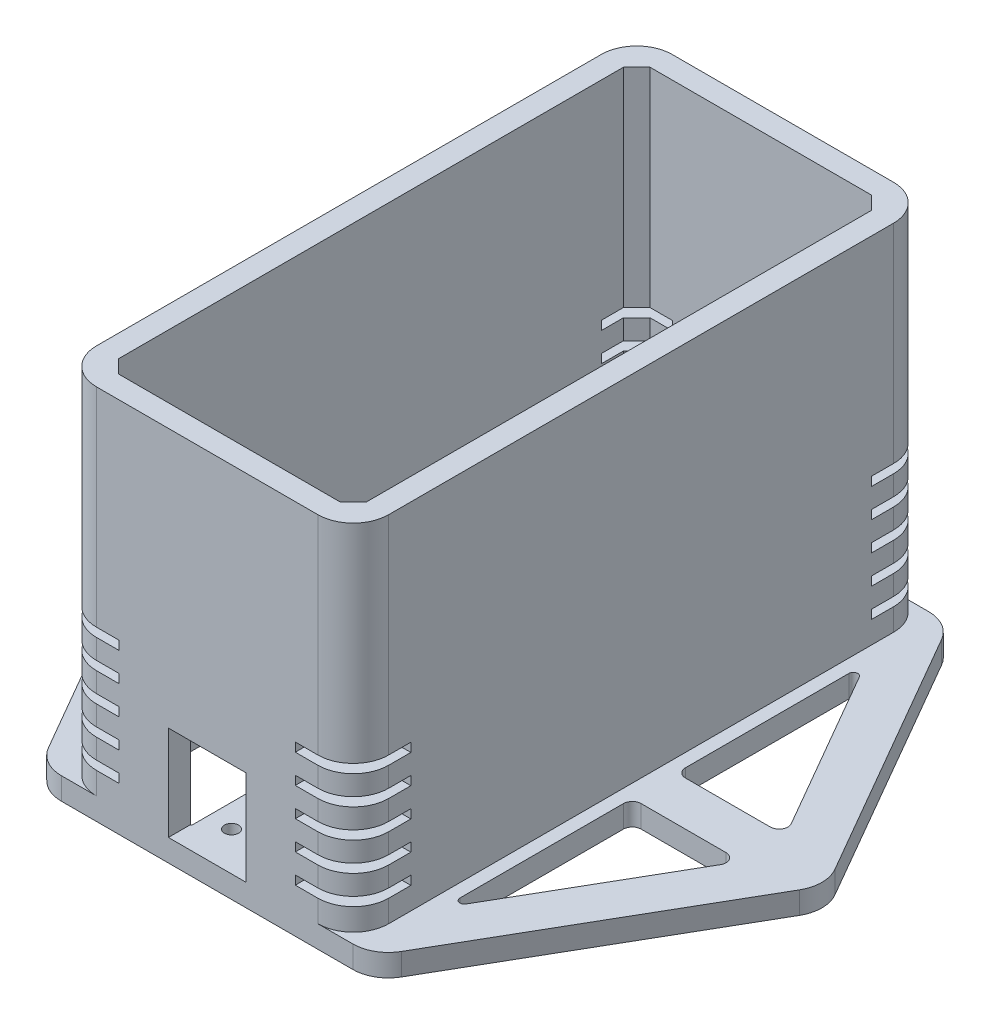
SolidWorks part; units mm, degrees
ref_plane "Front Plane" through (0, 0, 0) normal (0, 0, 1) x (1, 0, 0)
ref_plane "Top Plane" through (0, 0, 0) normal (0, 1, 0) x (1, 0, 0)
ref_plane "Right Plane" through (0, 0, 0) normal (1, 0, 0) x (0, 0, -1)
sketch "Sketch1" plane through (0, 0, 0) normal (0, 1, 0) x (1, 0, 0)
  line L1 (-75.0555, 0) -> (-37.5278, -65)
  line L2 (-37.5278, -65) -> (37.5278, -65)
  line L3 (37.5278, -65) -> (75.0555, 0)
  line L4 (75.0555, 0) -> (37.5278, 65)
  line L5 (37.5278, 65) -> (-37.5278, 65)
  line L6 (-37.5278, 65) -> (-75.0555, 0)
  circle A0 centre (0, 0) radius 65 construction
  circle A1 centre (0, 0) radius 50 construction
  dimension "D2" = 100
  dimension "D1" = 130
extrude "Boss-Extrude1" add sketch "Sketch1" along normal blind 5
fillet "Fillet1" radius 8 6 edges at (37.5278, 2.5, -65) (75.0555, 2.5, 0) (37.5278, 2.5, 65) (-37.5278, 2.5, 65) (-75.0555, 2.5, 0) (-37.5278, 2.5, -65)
sketch "Sketch3" plane through (0, 5, 0) normal (0, 1, 0) x (1, 0, 0)
  line L0 (-32.909, -65) -> (32.909, -65) construction
  line L1 (-25, 65) -> (25, 65)
  line L2 (-33, 57) -> (-33, -57)
  line L3 (-25, -65) -> (25, -65)
  line L4 (33, 57) -> (33, -57)
  line L5 (-33, 65) -> (33, -65) construction
  line L6 (-33, -65) -> (33, 65) construction
  arc A0 (33, 57) -> (25, 65) centre (25, 57) ccw
  arc A1 (33, -57) -> (25, -65) centre (25, -57) cw
  arc A2 (-25, -65) -> (-33, -57) centre (-25, -57) cw
  arc A3 (-25, 65) -> (-33, 57) centre (-25, 57) ccw
  point P0 (0, 0)
  dimension "D1" = 8
  dimension "D2" = 50
extrude "Boss-Extrude2" add sketch "Sketch3" along normal blind 80
sketch "Sketch4" plane through (0, 85, 0) normal (0, 1, 0) x (1, 0, 0)
  line L0 (-28, 57) -> (-25, 60)
  line L1 (25, 60) -> (28, 57)
  line L2 (28, -57) -> (25, -60)
  line L3 (-28, -57) -> (-25, -60)
  line L9 (-25, -60) -> (25, -60)
  line L10 (28, -57) -> (28, 57)
  line L11 (25, 60) -> (-25, 60)
  line L12 (-28, 57) -> (-28, -57)
  line L13 (-25, -60) -> (25, -60)
  line L14 (28, -57) -> (28, 57)
  line L15 (25, 60) -> (-25, 60)
  line L16 (-28, 57) -> (-28, -57)
  arc A9 (-28, -57) -> (-25, -60) centre (-25, -57) ccw
  arc A10 (25, -60) -> (28, -57) centre (25, -57) ccw
  arc A11 (28, 57) -> (25, 60) centre (25, 57) ccw
  arc A12 (-25, 60) -> (-28, 57) centre (-25, 57) ccw
  dimension "D1" = 5
extrude "Cut-Extrude1" cut sketch "Sketch4" against normal up to surface (85 mm away) up to face at (0, 0, 0)
sketch "Sketch8" plane through (0, 0, 0) normal (0, 1, 0) x (1, 0, 0)
  line L0 (0, 40) -> (0, 25) construction
  line L1 (0, 55) -> (0, 65) construction
  line L2 (9.5263, 26.5) -> (24.2487, 52) construction
  line L3 (22.5167, 55) -> (-22.5167, 55) construction
  line L4 (-24.2487, 52) -> (-9.5263, 26.5) construction
  line L5 (-12.5, 0) -> (-62.3346, 0) construction
  line L36 (6.9282, 25) -> (-6.9282, 25) construction
  line L37 (27.7128, 5) -> (57.1577, 5) construction
  line L38 (58.8897, 8) -> (36.3731, 47) construction
  line L39 (32.909, 47) -> (18.1865, 21.5) construction
  line L40 (25.1147, 6.5) -> (18.1865, 18.5) construction
  line L41 (18.1865, -21.5) -> (32.909, -47) construction
  line L42 (36.3731, -47) -> (58.8897, -8) construction
  line L43 (57.1577, -5) -> (27.7128, -5) construction
  line L44 (18.1865, -18.5) -> (25.1147, -6.5) construction
  line L45 (-9.5263, -26.5) -> (-24.2487, -52) construction
  line L46 (-22.5167, -55) -> (22.5167, -55) construction
  line L47 (24.2487, -52) -> (9.5263, -26.5) construction
  line L48 (-6.9282, -25) -> (6.9282, -25) construction
  line L49 (-27.7128, -5) -> (-57.1577, -5) construction
  line L50 (-58.8897, -8) -> (-36.3731, -47) construction
  line L51 (-32.909, -47) -> (-18.1865, -21.5) construction
  line L52 (-25.1147, -6.5) -> (-18.1865, -18.5) construction
  line L53 (-18.1865, 21.5) -> (-32.909, 47) construction
  line L54 (-37.866, 44.4141) -> (-58.8897, 8)
  line L55 (-57.1577, 5) -> (-38, 5)
  line L56 (-18.1865, 18.5) -> (-25.1147, 6.5) construction
  line L57 (-36, 7) -> (-36, 43.9141)
  line L58 (-33, 57) -> (-33, -57) construction
  line L59 (-36, -7) -> (-36, -43.9141)
  line L60 (-36.3731, 47) -> (-36, 47.6462) construction
  line L61 (-36, 5) -> (-27.7128, 5) construction
  line L71 (-33, 57) -> (-33, -57) construction
  line L72 (-57.1577, -5) -> (-38, -5)
  line L73 (-37.866, -44.4141) -> (-58.8897, -8)
  line L74 (37.866, -44.4141) -> (58.8897, -8)
  line L75 (57.1577, -5) -> (38, -5)
  line L76 (36, -7) -> (36, -43.9141)
  line L77 (36, 7) -> (36, 43.9141)
  line L78 (57.1577, 5) -> (38, 5)
  line L79 (37.866, 44.4141) -> (58.8897, 8)
  circle A0 centre (0, 0) radius 12.5 construction
  circle A1 centre (0, 40) radius 15 construction
  arc A3 (-22.5167, 55) -> (-24.2487, 52) centre (-22.5167, 53) ccw
  arc A4 (24.2487, 52) -> (22.5167, 55) centre (22.5167, 53) ccw construction
  arc A5 (6.9282, 25) -> (9.5263, 26.5) centre (6.9282, 28) ccw construction
  arc A6 (-6.9282, 25) -> (-9.5263, 26.5) centre (-6.9282, 28) cw construction
  arc A7 (25.1147, 6.5) -> (27.7128, 5) centre (27.7128, 8) ccw construction
  arc A8 (57.1577, 5) -> (58.8897, 8) centre (57.1577, 7) ccw construction
  arc A9 (36.3731, 47) -> (32.909, 47) centre (34.641, 46) ccw construction
  arc A10 (18.1865, 18.5) -> (18.1865, 21.5) centre (20.7846, 20) cw construction
  arc A11 (18.1865, -18.5) -> (18.1865, -21.5) centre (20.7846, -20) ccw construction
  arc A12 (32.909, -47) -> (36.3731, -47) centre (34.641, -46) ccw construction
  arc A13 (58.8897, -8) -> (57.1577, -5) centre (57.1577, -7) ccw construction
  arc A14 (25.1147, -6.5) -> (27.7128, -5) centre (27.7128, -8) cw construction
  arc A15 (-6.9282, -25) -> (-9.5263, -26.5) centre (-6.9282, -28) ccw construction
  arc A16 (-24.2487, -52) -> (-22.5167, -55) centre (-22.5167, -53) ccw construction
  arc A17 (22.5167, -55) -> (24.2487, -52) centre (22.5167, -53) ccw construction
  arc A18 (6.9282, -25) -> (9.5263, -26.5) centre (6.9282, -28) cw construction
  arc A19 (-25.1147, -6.5) -> (-27.7128, -5) centre (-27.7128, -8) ccw construction
  arc A20 (-57.1577, -5) -> (-58.8897, -8) centre (-57.1577, -7) ccw construction
  arc A21 (-36.3731, -47) -> (-32.909, -47) centre (-34.641, -46) ccw construction
  arc A22 (-18.1865, -18.5) -> (-18.1865, -21.5) centre (-20.7846, -20) cw construction
  arc A23 (-18.1865, 18.5) -> (-18.1865, 21.5) centre (-20.7846, 20) ccw construction
  arc A24 (-32.909, 47) -> (-36.3731, 47) centre (-34.641, 46) ccw construction
  arc A25 (-58.8897, 8) -> (-57.1577, 5) centre (-57.1577, 7) ccw
  arc A26 (-25.1147, 6.5) -> (-27.7128, 5) centre (-27.7128, 8) cw construction
  arc A28 (57.1577, -5) -> (58.8897, -8) centre (57.1577, -7) cw construction
  arc A31 (-36, 7) -> (-38, 5) centre (-38, 7) cw
  arc A32 (-36, 43.9141) -> (-37.866, 44.4141) centre (-37, 43.9141) ccw
  arc A33 (-36, -43.9141) -> (-37.866, -44.4141) centre (-37, -43.9141) cw
  arc A34 (-36, -7) -> (-38, -5) centre (-38, -7) ccw
  arc A35 (-58.8897, -8) -> (-57.1577, -5) centre (-57.1577, -7) cw
  arc A36 (57.1577, -5) -> (58.8897, -8) centre (57.1577, -7) cw construction
  arc A37 (58.8897, -8) -> (57.1577, -5) centre (57.1577, -7) ccw
  arc A38 (36, -7) -> (38, -5) centre (38, -7) cw
  arc A39 (36, -43.9141) -> (37.866, -44.4141) centre (37, -43.9141) ccw
  arc A40 (36, 43.9141) -> (37.866, 44.4141) centre (37, 43.9141) cw
  arc A41 (36, 7) -> (38, 5) centre (38, 7) ccw
  arc A42 (58.8897, 8) -> (57.1577, 5) centre (57.1577, 7) cw
  point P19 (0, 25)
  point P30 (0, 0)
  point P66 (0, 0)
  point P88 (0, 0)
  dimension "D1" = 25
  dimension "D3" = 30
  dimension "D6" = 2
  dimension "D8" = 3
  dimension "D11" = 2
  dimension "D12" = 1
  dimension "D2" = 40
  dimension "D4" = 10
  dimension "D5" = 15
  dimension "D7" = 25
  dimension "D9" = 3
extrude "Cut-Extrude2" cut sketch "Sketch8" along normal up to surface (5 mm away) up to face at (-41.2442, 5, 0)
ref_plane "Plane1" through (0, 10, 0) normal (0, 1, 0) x (1, 0, 0)
sketch "Sketch9" plane through (0, 10, 0) normal (0, 1, 0) x (1, 0, 0)
  line L0 (-32.909, -65) -> (-33.909, -65) construction
  line L6 (-33.909, -65) -> (-19.909, -65)
  line L7 (-33.909, -65) -> (-33.909, -52)
  line L8 (-33.909, -52) -> (-19.909, -52)
  line L9 (-19.909, -65) -> (-19.909, -52)
  line L10 (-33.909, -65) -> (-19.909, -52) construction
  line L11 (-33.909, -52) -> (-19.909, -65) construction
  point P7 (-26.909, -58.5)
  dimension "D1" = 1
  dimension "D2" = 13
  dimension "D3" = 14
extrude "Cut-Extrude3" cut sketch "Sketch9" along normal blind 2
pattern_linear "LPattern1" count 5 spacing 6.5 along (0, 1, 0) of "Cut-Extrude3"
mirror "Mirror1" about plane through (0, 0, 0) normal (1, 0, 0) of "LPattern1", "Cut-Extrude3"
sketch "Sketch10" plane through (0, 0, -60) normal (0, 0, 1) x (1, 0, 0)
  line L0 (-25, 0) -> (25, 0) construction
  line L1 (-8.5, 0) -> (8.5, 0)
  line L3 (-8.5, 5) -> (8.5, 5)
  line L4 (8.5, 0) -> (8.5, 5)
  line L5 (0, 0) -> (8.5, 5) construction
  line L6 (0, 5) -> (8.5, 0) construction
  line L7 (0, 0) -> (0, 5) construction
  line L8 (0, 5) -> (-8.5, 0) construction
  line L9 (0, 0) -> (-8.5, 5) construction
  line L10 (-8.5, 0) -> (-8.5, 5)
  point P4 (4.25, 2.5)
  point P9 (-4.25, 2.5)
  dimension "D1" = 8.5
extrude "Boss-Extrude3" add sketch "Sketch10" along normal up to surface (15 mm away)
sketch "Sketch11" plane through (0, 0, 0) normal (0, -1, 0) x (1, 0, 0)
  line L0 (3.25, -48.75) -> (8.5, -48.75) construction
  line L1 (3.25, -48.75) -> (3.25, -45) construction
  line L2 (0, -60) -> (0, -45) construction
  line L3 (-12.5, -52.5) -> (12.5, -52.5) construction
  line L4 (-8.5, -60) -> (8.5, -60) construction
  line L5 (-8.5, -45) -> (8.5, -45) construction
  line L6 (8.5, -45) -> (-8.5, -45) construction
  circle A0 centre (3.25, -56.25) radius 1.6
  circle A1 centre (-3.25, -56.25) radius 1.6
  circle A2 centre (-3.25, -48.75) radius 1.6
  circle A3 centre (3.25, -48.75) radius 1.6
  circle A4 centre (-3.25, -56.25) radius 3 construction
  dimension "D3" = 3.2
  dimension "D1" = 5.25
  dimension "D2" = 3.75
extrude "Cut-Extrude4" cut sketch "Sketch11" against normal blind 5
sketch "Sketch12" plane through (0, 0, -60) normal (0, 0, 1) x (1, 0, 0)
  line L0 (0, 0) -> (0, 5) construction
  line L1 (8.5, 0) -> (-8.5, 0) construction
  line L2 (-8.5, 5) -> (8.5, 5) construction
  line L3 (8.75, 5) -> (-8.75, 5)
  line L4 (-8.75, 5) -> (-8.75, 26.4)
  line L5 (-8.75, 26.4) -> (8.75, 26.4)
  line L6 (8.75, 5) -> (8.75, 26.4)
  point P10 (0, 26.4)
  dimension "D1" = 8.75
  dimension "D2" = 21.4
extrude "Cut-Extrude5" cut sketch "Sketch12" against normal up to surface and the other way up to surface up to face at (0, 23.75, -65) other way up to face at (0, 23.9583, 65)
sketch "Sketch14" plane through (0, 0, 60) normal (0, 0, -1) x (-1, 0, 0)
  line L0 (0, 0) -> (8.5, 0) construction
  line L1 (-25, 0) -> (25, 0) construction
  line L3 (8.5, 0) -> (-8.5, 0)
  line L4 (8.5, 0) -> (8.5, 5)
  line L5 (8.5, 5) -> (-8.5, 5)
  line L6 (-8.5, 0) -> (-8.5, 5)
  line L7 (8.5, 0) -> (-8.5, 5) construction
  line L8 (8.5, 5) -> (-8.5, 0) construction
  point P7 (0, 2.5)
extrude "Boss-Extrude4" add sketch "Sketch14" along normal up to surface (15 mm away)
sketch "Sketch16" plane through (0, 0, 0) normal (0, -1, 0) x (1, 0, 0)
  line L0 (3.25, 56.25) -> (8.5, 56.25) construction
  line L1 (3.25, 56.25) -> (3.25, 60) construction
  line L2 (0, 45) -> (0, 60) construction
  line L3 (-12.5, 52.5) -> (12.5, 52.5) construction
  line L4 (-8.5, 45) -> (8.5, 45) construction
  line L5 (8.5, 45) -> (-8.5, 45) construction
  line L6 (-3.25, 48.75) -> (-3.25, 45) construction
  line L7 (-3.25, 48.75) -> (-8.5, 48.75) construction
  line L8 (8.5, 45) -> (-8.5, 45) construction
  line L9 (-8.5, 45) -> (8.5, 45) construction
  line L10 (8.5, 45) -> (8.5, 60) construction
  line L11 (-8.5, 45) -> (-8.5, 60) construction
  circle A0 centre (3.25, 48.75) radius 1.6
  circle A1 centre (-3.25, 48.75) radius 1.6
  circle A2 centre (-3.25, 56.25) radius 1.6
  circle A3 centre (3.25, 56.25) radius 1.6
  circle A4 centre (-3.25, 48.75) radius 3 construction
  dimension "D1" = 3.2
  dimension "D2" = 5.25
  dimension "D3" = 3.75
extrude "Cut-Extrude6" cut sketch "Sketch16" against normal blind 5
mirror "Mirror2" about plane through (0, 0, 0) normal (0, 0, 1) of "Mirror1", "Cut-Extrude3", "LPattern1"
